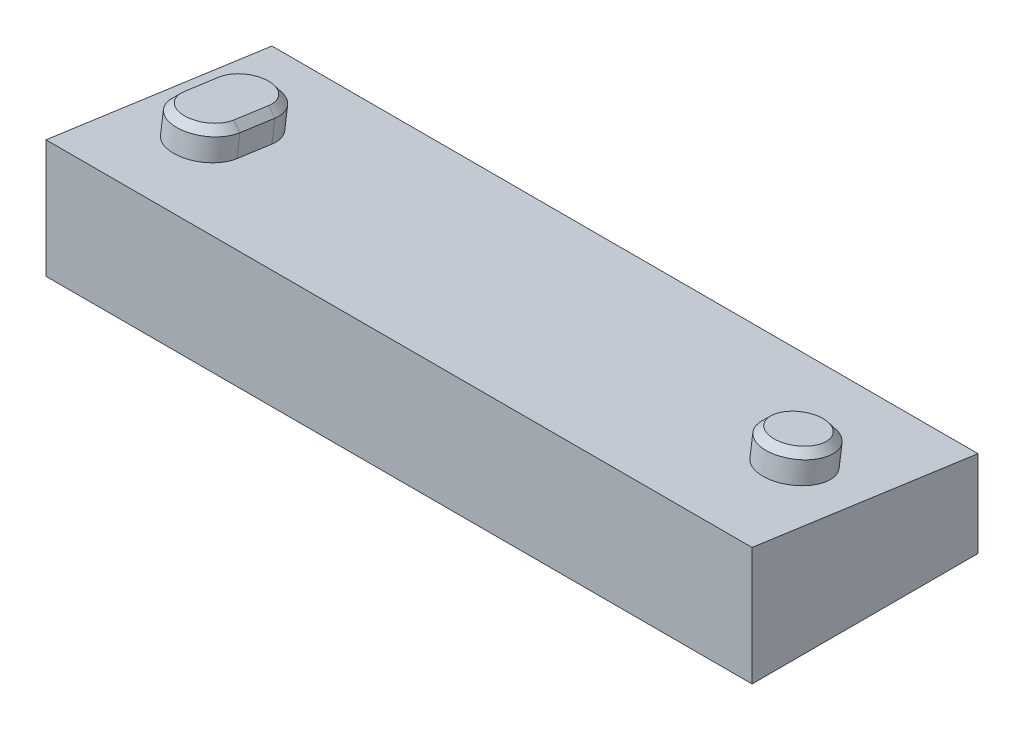
SolidWorks part; units mm, degrees
material "AISI 1010 钢，热轧条材"
ref_plane "前视基准面" through (0, 0, 0) normal (0, 0, 1) x (1, 0, 0)
ref_plane "上视基准面" through (0, 0, 0) normal (0, 1, 0) x (1, 0, 0)
ref_plane "右视基准面" through (0, 0, 0) normal (1, 0, 0) x (0, 0, -1)
sketch "草图1" plane through (0, 0, 0) normal (0, 0, 1) x (1, 0, 0)
  line L0 (-17, -12.9904) -> (-17, -66.8639)
  line L1 (-20.5, -12.9904) -> (-20.5, -66.8639)
  line L2 (-17, -66.8639) -> (-20.5, -66.8639)
  line L3 (0, 7.4816) -> (0, 50007.4816) construction
  line L4 (17, -66.8639) -> (20.5, -66.8639)
  line L5 (20.5, -12.9904) -> (20.5, -66.8639)
  line L6 (17, -12.9904) -> (17, -66.8639)
  arc A0 (-13.3571, -10.516) -> (13.3571, -10.516) centre (0, 0) ccw
  arc A1 (-16.1071, -12.6811) -> (16.1071, -12.6811) centre (0, 0) ccw
  arc A2 (-13.3571, -10.516) -> (-20.5, -12.9904) centre (-16.5, -12.9904) ccw
  circle A3 centre (0, 0) radius 17 construction
  circle A4 centre (0, 0) radius 20.5 construction
  arc A5 (-16.1071, -12.6811) -> (-17, -12.9904) centre (-16.5, -12.9904) ccw
  arc A6 (16.1071, -12.6811) -> (17, -12.9904) centre (16.5, -12.9904) cw
  arc A7 (13.3571, -10.516) -> (20.5, -12.9904) centre (16.5, -12.9904) cw
  point P1 (20.5, 0)
  point P4 (16.2572, 4.9703)
  point P15 (20.5, 0)
  point P18 (16.2572, 4.9703)
  dimension "D1" = 3.5
  dimension "D2" = 4
  dimension "D3" = 17
  dimension "D4" = 3.5
extrude "凸台-拉伸1" add sketch "草图1" along normal mid plane 32
sketch "草图2" plane through (0, 0, 0) normal (1, 0, 0) x (0, 0, -1)
  line L0 (0, 0) -> (50000, 0) construction
  line L1 (0, 0) -> (0, -50000) construction
  line L2 (29.9617, -62.7108) -> (0, -58.5) construction
  line L3 (16, -60.7487) -> (-16, -56.2513)
  line L4 (16, -66.8639) -> (16, -12.9904) construction
  line L5 (-16, -66.8639) -> (-16, -12.9904) construction
  line L6 (-16, -56.2513) -> (-16, -66.8639)
  line L7 (-16, -66.8639) -> (16, -66.8639)
  line L8 (16, -66.8639) -> (16, -60.7487)
  dimension "D1" = 8
  dimension "D2" = 58.5
extrude "切除-拉伸1" cut sketch "草图2" against normal mid plane 100
sketch "草图3" plane through (-20.5, 0, 0) normal (-1, 0, 0) x (0, 0, 1)
  line L0 (-16, -60.7487) -> (16, -56.2513)
  line L1 (-16, -57.2143) -> (16, -52.717)
  line L2 (16, -12.9904) -> (16, -56.2513) construction
  line L4 (-16, -60.7487) -> (-16, -57.2143)
  line L5 (16, -56.2513) -> (16, -52.717)
  line L7 (-16.4871, -57.2827) -> (15.5129, -52.7854) construction
  dimension "D1" = 3.5
extrude "凸台-拉伸2" add sketch "草图3" along normal blind 28.5
mirror "镜向1" about plane through (0, 0, 0) normal (1, 0, 0) of "凸台-拉伸2"
sketch "草图4" plane through (0, -53.901, 7.5753) normal (0, 0.9903, -0.1392) x (1, 0, 0)
  line L0 (0, 0) -> (0, -50000) construction
  line L1 (-49, 7.6497) -> (49, 7.6497) construction
  line L2 (-49, -8.5075) -> (-49, 23.807) construction
  line L3 (49, -8.5075) -> (49, 23.807) construction
  line L4 (-40.5, 23.807) -> (-40.5, -8.5075) construction
  line L5 (-49, 23.807) -> (-20.5, 23.807) construction
  line L6 (-49, -8.5075) -> (-20.5, -8.5075) construction
  line L7 (40.5, 23.807) -> (40.5, -8.5075) construction
  line L8 (-36, 10.1497) -> (-36, 5.1497)
  line L9 (-45, 10.1497) -> (-45, 5.1497)
  arc A0 (-36, 10.1497) -> (-45, 10.1497) centre (-40.5, 10.1497) ccw
  arc A1 (-45, 5.1497) -> (-36, 5.1497) centre (-40.5, 5.1497) ccw
  circle A2 centre (40.5, 7.6497) radius 4.5
  dimension "D2" = 9
  dimension "D4" = 9
  dimension "D1" = 81
  dimension "D3" = 5
extrude "切除-拉伸2" cut sketch "草图4" against normal blind 28.5
sketch "草图5" plane through (0, 0, 0) normal (1, 0, 0) x (0, 0, -1)
  line L0 (-16, -56.2513) -> (16, -60.7487)
  line L1 (16, -60.7487) -> (16, -72.9987)
  line L2 (16, -72.9987) -> (-16, -72.9987)
  line L3 (-16, -72.9987) -> (-16, -56.2513)
  dimension "D1" = 12.25
extrude "凸台-拉伸3" add sketch "草图5" along normal mid plane 100 separate body
sketch "草图6" plane through (0, -57.3669, 8.0624) normal (0, 0.9903, -0.1392) x (1, 0, 0)
  line L6 (-36, 5.1497) -> (-36, 10.1497)
  line L7 (-36, 5.1497) -> (-36, 10.1497)
  line L9 (-45, 10.1497) -> (-45, 5.1497)
  line L10 (-45, 10.1497) -> (-45, 5.1497)
  line L14 (0, 0) -> (0, 50000) construction
  circle A0 centre (40.5, 7.6497) radius 4.5
  arc A3 (-36, 10.1497) -> (-45, 10.1497) centre (-40.5, 10.1497) ccw
  arc A4 (-36, 10.1497) -> (-45, 10.1497) centre (-40.5, 10.1497) ccw
  arc A6 (-45, 5.1497) -> (-36, 5.1497) centre (-40.5, 5.1497) ccw
  arc A7 (-45, 5.1497) -> (-36, 5.1497) centre (-40.5, 5.1497) ccw
  dimension "D1" = 0
  dimension "D2" = 0
  dimension "D3" = 0
  dimension "D4" = 0
extrude "凸台-拉伸4" add sketch "草图6" along normal blind 4
sketch "草图7" plane through (0, 0, 0) normal (1, 0, 0) x (0, 0, -1)
  line L0 (16, -60.7487) -> (-16, -56.2513)
  line L1 (-16, -56.2513) -> (-16, -52.717) construction
  line L2 (16, -60.7487) -> (-16, -56.2513) construction
  line L3 (-16, -56.2513) -> (-16, 0)
  line L4 (-16, 0) -> (16, 0)
  line L5 (16, 0) -> (16, -60.7487)
extrude "切除-拉伸3" cut sketch "草图7" against normal mid plane 120
chamfer "倒角1" distance 1 angle 45 5 edges at (40.5, -53.8442, 4.3866) (-40.5, -55.4447, -7.0015) (-45, -54.4705, -0.0696) (-36, -54.4705, -0.0696) (-40.5, -53.4963, 6.8623)
